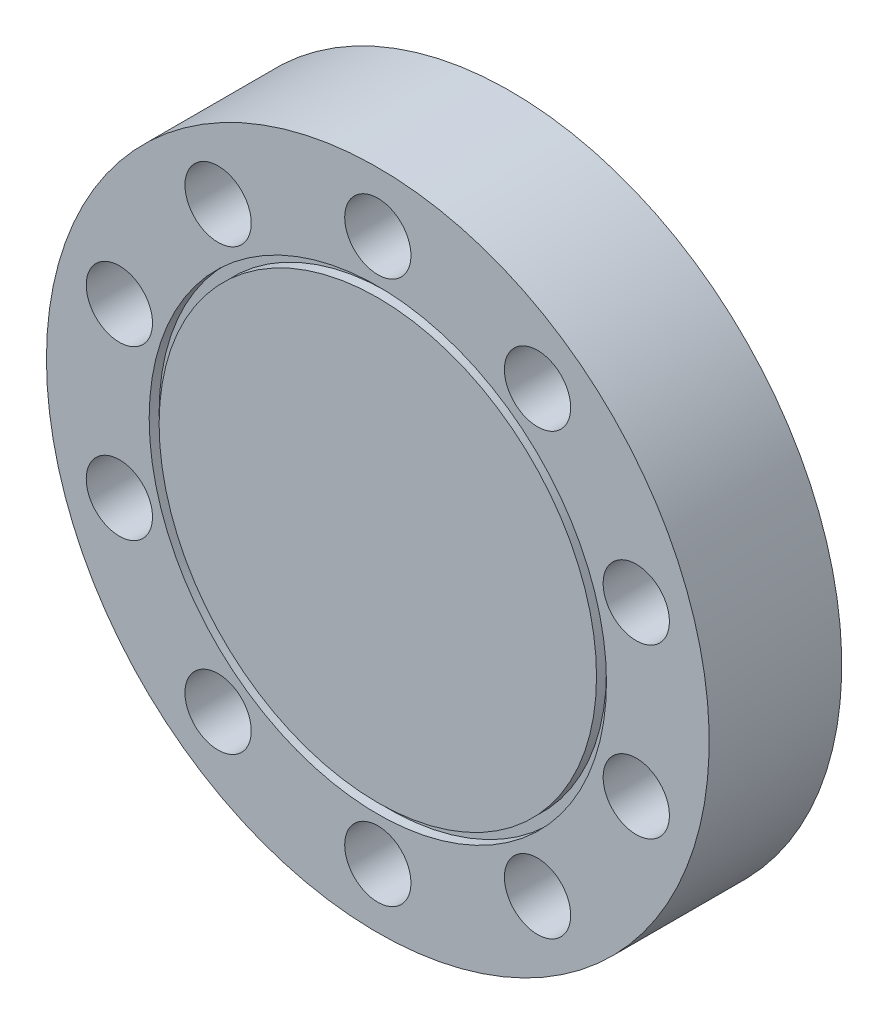
SolidWorks part; units mm, degrees
material "1.0050 (E295)"
ref_plane "Front Plane" through (0, 0, 0) normal (0, 0, 1) x (1, 0, 0)
ref_plane "Top Plane" through (0, 0, 0) normal (0, 1, 0) x (1, 0, 0)
ref_plane "Right Plane" through (0, 0, 0) normal (1, 0, 0) x (0, 0, -1)
sketch "Sketch1" plane through (0, 0, 0) normal (0, 0, 1) x (1, 0, 0)
  circle A0 centre (0, 0) radius 41 construction
  circle A1 centre (0, 0) radius 50
  circle A2 centre (0, -41) radius 5
  circle A3 centre (-24.0992, -33.1697) radius 5
  circle A4 centre (-38.9933, -12.6697) radius 5
  circle A5 centre (-38.9933, 12.6697) radius 5
  circle A6 centre (-24.0992, 33.1697) radius 5
  circle A7 centre (0, 41) radius 5
  circle A8 centre (24.0992, 33.1697) radius 5
  circle A9 centre (38.9933, 12.6697) radius 5
  circle A10 centre (38.9933, -12.6697) radius 5
  circle A11 centre (24.0992, -33.1697) radius 5
  point P27 (0, 0)
  dimension "D1" = 100
  dimension "D2" = 82
  dimension "D4" = 10
  dimension "D3" = 10
extrude "Boss-Extrude1" add sketch "Sketch1" along normal blind 20
sketch "Sketch2" plane through (0, 0, 20) normal (0, 0, 1) x (1, 0, 0)
  circle A0 centre (0, 0) radius 34.5
  circle A1 centre (0, 0) radius 33
  dimension "D1" = 69
  dimension "D2" = 66
extrude "Cut-Extrude1" cut sketch "Sketch2" against normal blind 1.5
